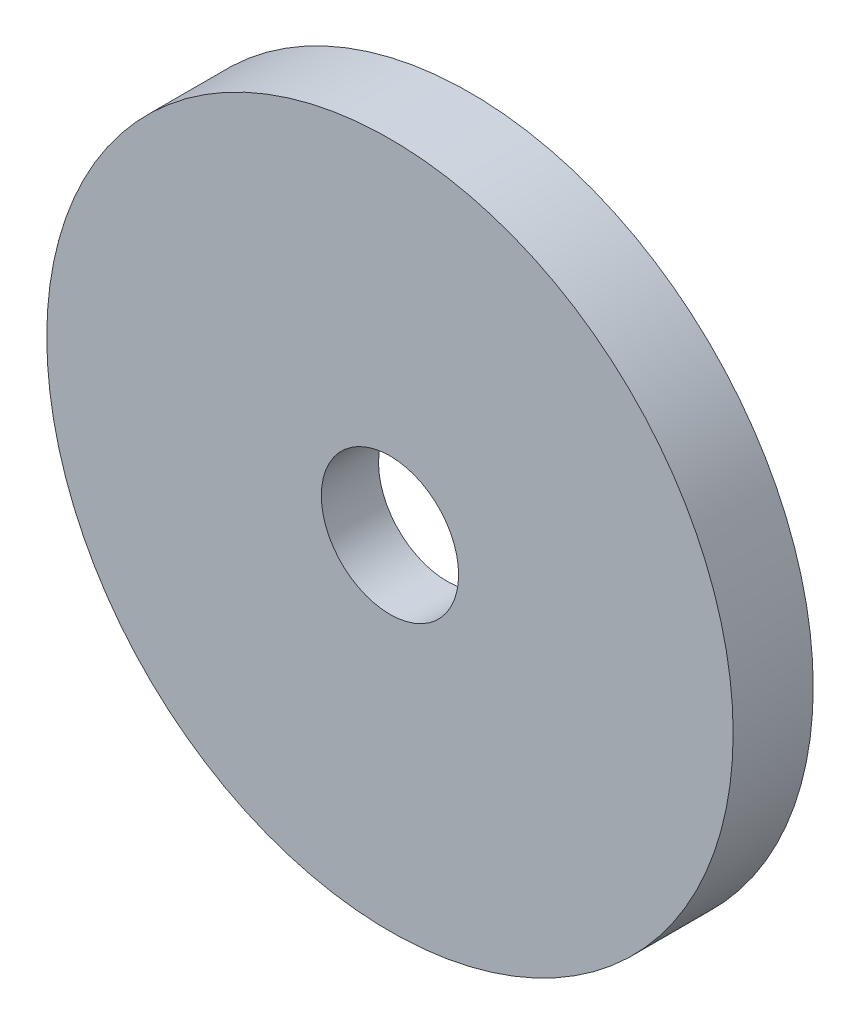
SolidWorks part; units mm, degrees
ref_plane "Front Plane" through (0, 0, 0) normal (0, 0, 1) x (1, 0, 0)
ref_plane "Top Plane" through (0, 0, 0) normal (0, 1, 0) x (1, 0, 0)
ref_plane "Right Plane" through (0, 0, 0) normal (1, 0, 0) x (0, 0, -1)
sketch "Sketch2" plane through (0, 0, 0) normal (0, 0, 1) x (1, 0, 0)
  circle A0 centre (0, 0) radius 30
  dimension "D1" = 60
extrude "Boss-Extrude1" add sketch "Sketch2" along normal blind 6 contours A0
sketch "Sketch3" plane through (0, 0, 0) normal (0, 0, -1) x (-1, 0, 0)
  circle A0 centre (0, 0) radius 8
extrude "Cut-Extrude1" cut sketch "Sketch3" against normal blind 2
sketch "Sketch4" plane through (0, 0, 2) normal (0, 0, -1) x (-1, 0, 0)
  circle A0 centre (0, 0) radius 6
  dimension "D1" = 12
extrude "Cut-Extrude2" cut sketch "Sketch4" against normal blind 5
sketch "Sketch5" plane through (0, 0, 0) normal (0, 0, -1) x (-1, 0, 0)
  circle A0 centre (0, 0) radius 8
  circle A1 centre (0, 0) radius 30
extrude "Cut-Extrude3" cut sketch "Sketch5" against normal blind 2
sketch "Sketch7" plane through (0, 0, 2) normal (0, 0, -1) x (-1, 0, 0)
  circle A0 centre (0, 0) radius 30 construction
  circle A1 centre (0, 0) radius 30
  circle A2 centre (0, 0) radius 20
extrude "Boss-Extrude3" add sketch "Sketch7" along normal blind 3
sketch "Sketch8" plane through (0, 0, 2) normal (0, 0, -1) x (-1, 0, 0)
  circle A0 centre (0, 0) radius 6 construction
  circle A1 centre (0, 0) radius 20
  circle A2 centre (0, 0) radius 20
  circle A3 centre (0, 0) radius 6
  dimension "D1" = 0
extrude "Boss-Extrude4" add sketch "Sketch8" along normal blind 1
sketch "Sketch9" plane through (0, 0, 0) normal (0, 1, 0) x (1, 0, 0)
  line L0 (23, 4.4385) -> (23, -9.579) construction
  line L1 (30, -6) -> (30, 4.4385) construction
  line L2 (-30, -6) -> (30, -6) construction
  line L4 (25, 16.5) -> (21, 16.5)
  line L5 (25, 16.5) -> (25, -3.5)
  line L6 (25, -3.5) -> (21, -3.5)
  line L7 (21, 16.5) -> (21, -3.5)
  line L8 (27.6, -3.5) -> (18.4, -3.5)
  line L9 (27.6, -3.5) -> (27.6, -4.2352)
  line L10 (27.6, -4.2352) -> (18.4, -4.2352)
  line L11 (18.4, -3.5) -> (18.4, -4.2352)
  dimension "D1" = 7
  dimension "D2" = 4
  dimension "D3" = 9.2
  dimension "D4" = 2.5
  dimension "D5" = 20
sketch "Sketch10" plane through (0, 0, -1) normal (0, 1, 0) x (1, 0, 0)
  line L0 (-30, -7) -> (30, -7) construction
  line L1 (27.8253, -7) -> (21.2987, -7)
  line L2 (27.8253, -7) -> (27.8253, 17.914)
  line L3 (27.8253, 17.914) -> (21.2987, 17.914)
  line L4 (21.2987, -7) -> (21.2987, 17.914)
sketch "Sketch11" plane through (0, 0, -1) normal (0, 1, 0) x (1, 0, 0)
  line L0 (23, 25.9336) -> (23, -31.2164) construction
  line L1 (30, -7) -> (30, -4.13) construction
  line L2 (27.6, -4.7176) -> (18.4, -4.7176)
  line L3 (27.6, -4.7176) -> (27.6, -4.5)
  line L4 (27.6, -4.5) -> (18.4, -4.5)
  line L5 (18.4, -4.7176) -> (18.4, -4.5)
  line L6 (25.5, -4.5) -> (20.5, -4.5)
  line L7 (25.5, -4.5) -> (25.5, 15.5)
  line L8 (25.5, 15.5) -> (20.5, 15.5)
  line L9 (20.5, -4.5) -> (20.5, 15.5)
  line L10 (-30, -7) -> (30, -7) construction
  line L11 (30, -5.565) -> (30, 15.8013) construction
  line L12 (20.026, -1.9778) -> (20.026, 1.2006) construction
  dimension "D1" = 9.2
  dimension "D2" = 20
  dimension "D3" = 5
  dimension "D4" = 7
  dimension "D5" = 2.5
  dimension "D6" = 0.474
